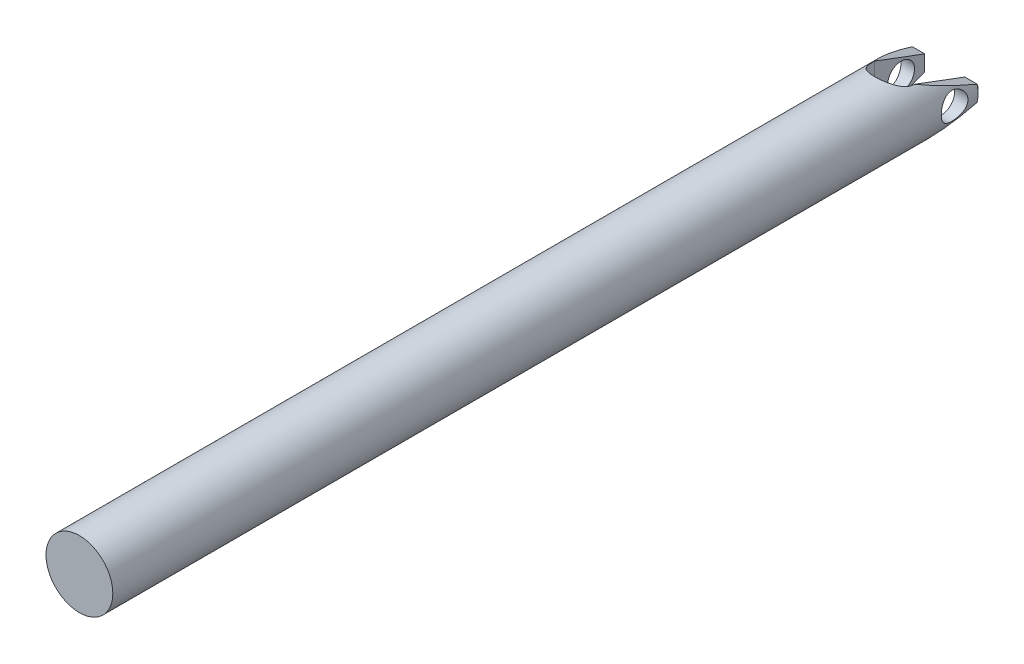
SolidWorks part; units mm, degrees
ref_plane "Front Plane" through (0, 0, 0) normal (0, 0, 1) x (1, 0, 0)
ref_plane "Top Plane" through (0, 0, 0) normal (0, 1, 0) x (1, 0, 0)
ref_plane "Right Plane" through (0, 0, 0) normal (1, 0, 0) x (0, 0, -1)
sketch "Sketch1" plane through (0, 0, 0) normal (0, 0, 1) x (1, 0, 0)
  circle A0 centre (0, 0) radius 5
  dimension "D1" = 10
extrude "Boss-Extrude1" add sketch "Sketch1" along normal blind 130
ref_plane "Plane1" through (0, 5, 0) normal (0, 1, 0) x (1, 0, 0)
sketch "Sketch2" plane through (0, 5, 0) normal (0, 1, 0) x (1, 0, 0)
  line L0 (-5, 0) -> (5, 0) construction
  line L1 (5, 0) -> (-5, 0) construction
  line L2 (-3, 0) -> (3, 0)
  line L4 (-3, 0) -> (-3, -8)
  line L6 (3, 0) -> (3, -8)
  arc A0 (-3, -8) -> (3, -8) centre (0, -8) ccw
  dimension "D1" = 6
  dimension "D2" = 8
extrude "Cut-Extrude1" cut sketch "Sketch2" against normal through all
ref_plane "Plane2" through (5, 0, 0) normal (1, 0, 0) x (0, 0, -1)
sketch "Sketch3" plane through (5, 0, 0) normal (1, 0, 0) x (0, 0, -1)
  line L0 (0, 0) -> (-130, 0) construction
  line L1 (-130, 5) -> (-130, -5) construction
  line L2 (0, 4) -> (-8, 4) construction
  line L3 (-8, 4) -> (-8, -4) construction
  line L4 (-8, -4) -> (0, -4) construction
  line L5 (-8, -4) -> (0, -1)
  line L6 (0, -4) -> (0, 4) construction
  line L7 (0, -1) -> (0, -4)
  line L8 (0, -4) -> (-8, -4)
  line L9 (0, 1) -> (0, 4)
  line L10 (-8, 4) -> (0, 1)
  line L11 (0, 4) -> (-8, 4)
  circle A0 centre (-4, 0) radius 2
  dimension "D1" = 4
  dimension "D2" = 4
  dimension "D3" = 3
extrude "Cut-Extrude2" cut sketch "Sketch3" against normal through all
chamfer "Chamfer1" distance 0.5 distance2 0.5 8 edges at (-3.9495, -1, 0) (-5, 0, 0) (5, 0, 0) (-3.9495, 1, 0) (-3, 0, 0) (3, 0, 0) (3.9495, -1, 0) (3.9495, 1, 0)
